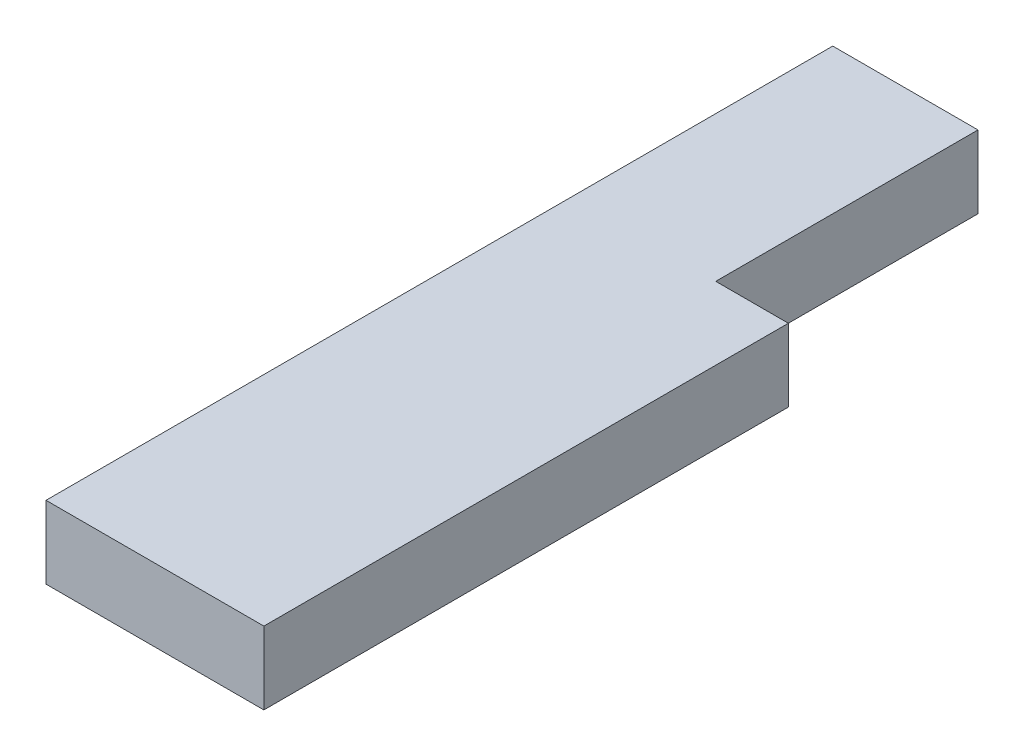
SolidWorks part; units mm, degrees
ref_plane "Front Plane" through (0, 0, 0) normal (0, 0, 1) x (1, 0, 0)
ref_plane "Top Plane" through (0, 0, 0) normal (0, 1, 0) x (1, 0, 0)
ref_plane "Right Plane" through (0, 0, 0) normal (1, 0, 0) x (0, 0, -1)
sketch "Sketch1" plane through (0, 0, 0) normal (0, 0, 1) x (1, 0, 0)
  line L1 (-27, -9) -> (27, -9)
  line L2 (-27, -9) -> (-27, 9)
  line L3 (-27, 9) -> (27, 9)
  line L4 (27, -9) -> (27, 9)
  line L5 (0, 9) -> (0, -9) construction
  line L6 (-27, 0) -> (27, 0) construction
  point P0 (0, 0)
  dimension "D1" = 18
  dimension "D2" = 54
extrude "Boss-Extrude1" add sketch "Sketch1" along normal blind 130 contours L3 L4 L1 L2
sketch "Sketch4" plane through (0, 0, 0) normal (0, 0, -1) x (-1, 0, 0)
  line L0 (-9, 9) -> (-9, -9)
  line L4 (27, -9) -> (27, 9)
  line L5 (27, 9) -> (-27, 9)
  line L6 (-27, 9) -> (-27, -9)
  line L7 (-27, -9) -> (27, -9)
  line L8 (27, -9) -> (27, 9)
  line L9 (27, 9) -> (-9, 9)
  line L11 (-9, -9) -> (27, -9)
  dimension "D2" = 36
  dimension "D1" = 0
extrude "Boss-Extrude3" add sketch "Sketch4" along normal blind 65
